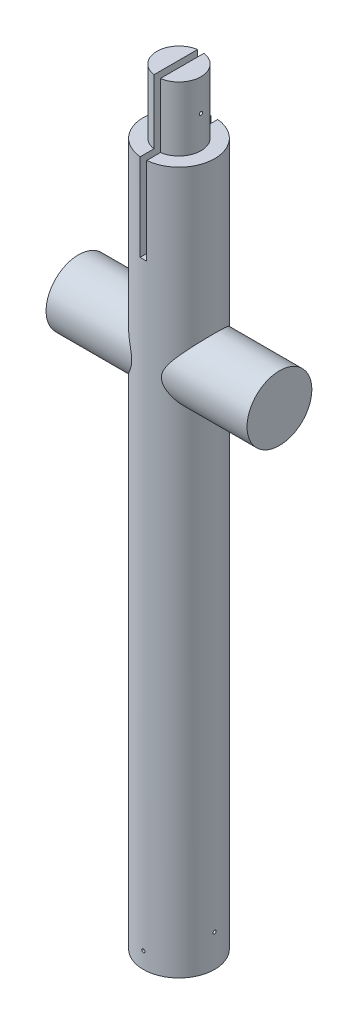
SolidWorks part; units mm, degrees
ref_plane "Front Plane" through (0, 0, 0) normal (0, 0, 1) x (1, 0, 0)
ref_plane "Top Plane" through (0, 0, 0) normal (0, 1, 0) x (1, 0, 0)
ref_plane "Right Plane" through (0, 0, 0) normal (1, 0, 0) x (0, 0, -1)
sketch "Sketch1" plane through (0, 0, 0) normal (0, 1, 0) x (1, 0, 0)
  circle A0 centre (0, 0) radius 11
extrude "Boss-Extrude1" add sketch "Sketch1" along normal blind 216.6667 contours A0
sketch "Sketch2" plane through (0, 0, 0) normal (0, 1, 0) x (1, 0, 0)
  circle A0 centre (0, 0) radius 6.8
extrude "Boss-Extrude2" add sketch "Sketch2" along normal blind 19.8 from offset 216.6667
sketch "Sketch4" plane through (0, 0, 0) normal (1, 0, 0) x (0, 0, -1)
  line L2 (0, 12.1) -> (0, -12.1) construction
  circle A0 centre (0, 226.6667) radius 0.5
extrude "Cut-Extrude2" cut sketch "Sketch4" against normal blind 9 from offset 1.4 offset against normal yes
mirror "Mirror2" about plane through (0, 0, 0) normal (1, 0, 0) of "Cut-Extrude2"
sketch "Sketch6" plane through (0, 0, 0) normal (0, 1, 0) x (1, 0, 0)
  circle A0 centre (0, 0) radius 7
extrude "Cut-Extrude3" cut sketch "Sketch6" along normal blind 20
sketch "Sketch7" plane through (0, 0, 0) normal (1, 0, 0) x (0, 0, -1)
  line L1 (0, 12.1) -> (0, -12.1) construction
  circle A0 centre (0, 10) radius 0.5
extrude "Cut-Extrude4" cut sketch "Sketch7" against normal through all both and the other way through all
sketch "Sketch10" plane through (0, 0, 0) normal (0, 0, 1) x (1, 0, 0)
  line L1 (0, -12.1) -> (0, 12.1) construction
  circle A0 centre (0, 5) radius 0.5
extrude "Cut-Extrude5" cut sketch "Sketch10" against normal through all both and the other way through all
sketch "Sketch11" plane through (0, 0, 0) normal (0, 0, 1) x (1, 0, 0)
  line L8 (6.8, 236.4667) -> (-6.8, 236.4667) construction
  line L13 (-1, 189.7865) -> (1, 189.7865)
  line L14 (-1, 189.7865) -> (-1, 236.4667)
  line L15 (1, 189.7865) -> (1, 236.4667)
  line L16 (-1, 236.4667) -> (1, 236.4667)
extrude "Cut-Extrude6" cut sketch "Sketch11" against normal through all both and the other way through all
sketch "Sketch14" plane through (0, 0, 0) normal (1, 0, 0) x (0, 0, -1)
  line L2 (0, 12.1) -> (0, -12.1) construction
  circle A0 centre (0, 160) radius 10
extrude "Boss-Extrude3" add sketch "Sketch14" along normal blind 28.5 from offset 2.5
mirror "Mirror3" about plane through (0, 0, 0) normal (1, 0, 0) of "Boss-Extrude3"
equation "\"V\"=0"
